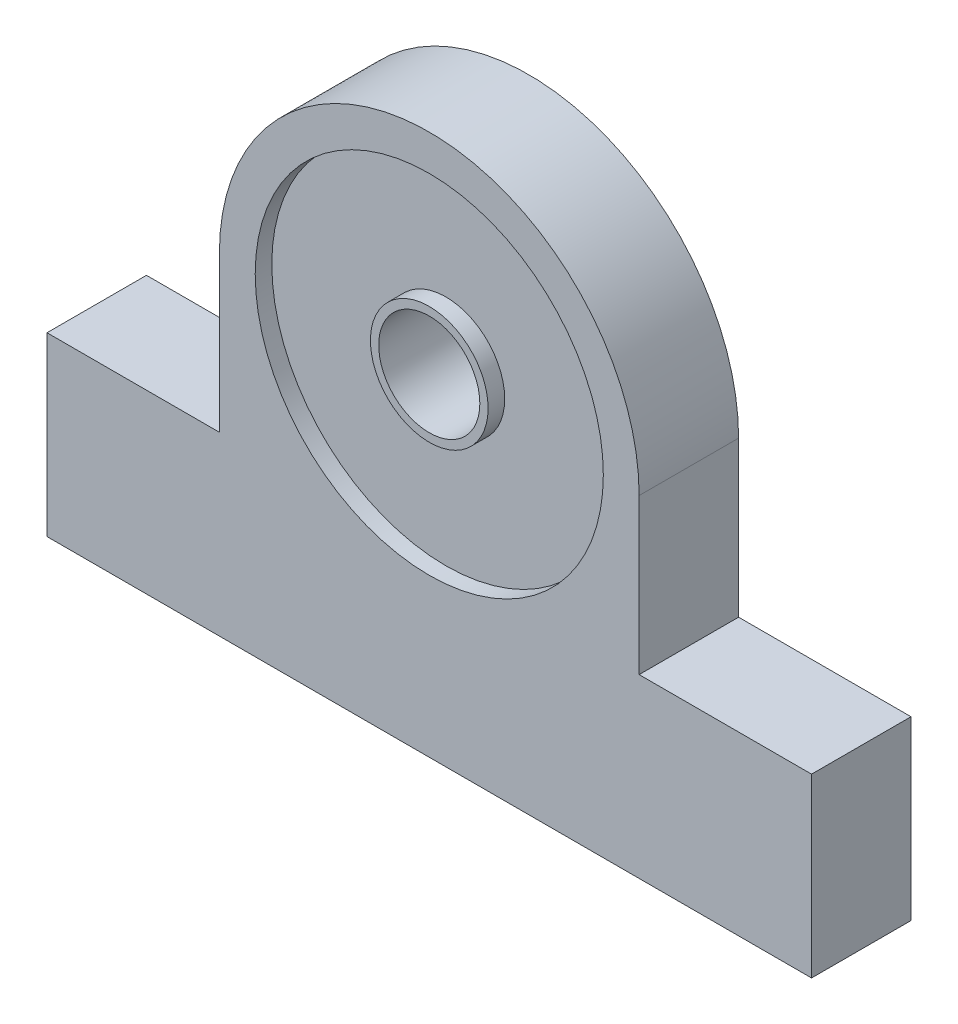
SolidWorks part; units mm, degrees
ref_plane "Front Plane" through (0, 0, 0) normal (0, 0, 1) x (1, 0, 0)
ref_plane "Top Plane" through (0, 0, 0) normal (0, 1, 0) x (1, 0, 0)
ref_plane "Right Plane" through (0, 0, 0) normal (1, 0, 0) x (0, 0, -1)
sketch "Sketch1" plane through (0, 0, 0) normal (0, 0, 1) x (1, 0, 0)
  circle A0 centre (0, 0) radius 11
  circle A1 centre (0, 0) radius 3
  dimension "D1" = 22
  dimension "D2" = 6
extrude "Boss-Extrude2" add sketch "Sketch1" along normal blind 6
sketch "Sketch3" plane through (0, 0, 6) normal (0, 0, 1) x (1, 0, 0)
  circle A0 centre (0, 0) radius 3.55
  circle A1 centre (0, 0) radius 10.5
  dimension "D1" = 7.1
  dimension "D2" = 21
extrude "Cut-Extrude1" cut sketch "Sketch3" against normal blind 1 contours A1
sketch "Sketch4" plane through (0, 0, 5) normal (0, 0, 1) x (1, 0, 0)
  circle A0 centre (0, 0) radius 3.55
  dimension "D1" = 7.1
extrude "Boss-Extrude5" add sketch "Sketch4" along normal blind 1
sketch "Sketch5" plane through (0, 0, 6) normal (0, 0, 1) x (1, 0, 0)
  circle A0 centre (0, 0) radius 3.05
  dimension "D1" = 6.1
extrude "Cut-Extrude2" cut sketch "Sketch5" against normal through all contours A0
sketch "Sketch6" plane through (0, 0, 0) normal (0, 0, -1) x (-1, 0, 0)
  circle A0 centre (0, 0) radius 3.55
  dimension "D1" = 7.1
extrude "Boss-Extrude6" add sketch "Sketch6" along normal blind 2
sketch "Sketch7" plane through (0, 0, -2) normal (0, 0, -1) x (-1, 0, 0)
  circle A0 centre (0, 0) radius 3.05
  dimension "D1" = 6.1
extrude "Cut-Extrude3" cut sketch "Sketch7" against normal through all contours A0
sketch "Sketch9" plane through (0, 0, 0) normal (0, 0, 1) x (1, 0, 0)
  line L0 (-12.6606, 0) -> (-12.6606, -9.3549)
  line L1 (-12.6606, -9.3549) -> (-23.0606, -9.3549)
  line L2 (-23.0606, -9.3549) -> (-23.0606, -15.3549)
  line L3 (-23.0606, -15.3549) -> (23.0606, -15.3549)
  line L4 (23.0606, -15.3549) -> (23.0606, -9.3549)
  line L5 (23.0606, -9.3549) -> (12.6606, -9.3549)
  line L6 (12.6606, -9.3549) -> (12.6606, 0)
  arc A0 (12.6606, 0) -> (-12.6606, 0) centre (0, 0) ccw
  circle A1 centre (0, 0) radius 11
  dimension "D4" = 22
  dimension "D1" = 10.4
  dimension "D2" = 10.4
  dimension "D3" = 6
extrude "Boss-Extrude9" add sketch "Sketch9" along normal through all
sketch "Sketch10" plane through (0, 0, 0) normal (0, 0, 1) x (1, 0, 0)
  line L1 (-23.0606, -15.3549) -> (23.0606, -15.3549)
  line L2 (-23.0606, -15.3549) -> (-23.0606, -20.0049)
  line L3 (-23.0606, -20.0049) -> (23.0606, -20.0049)
  line L4 (23.0606, -15.3549) -> (23.0606, -20.0049)
  dimension "D1" = 4.65
extrude "Boss-Extrude10" add sketch "Sketch10" along normal up to surface (6 mm away) up to face at (10.5, 0, 6)
